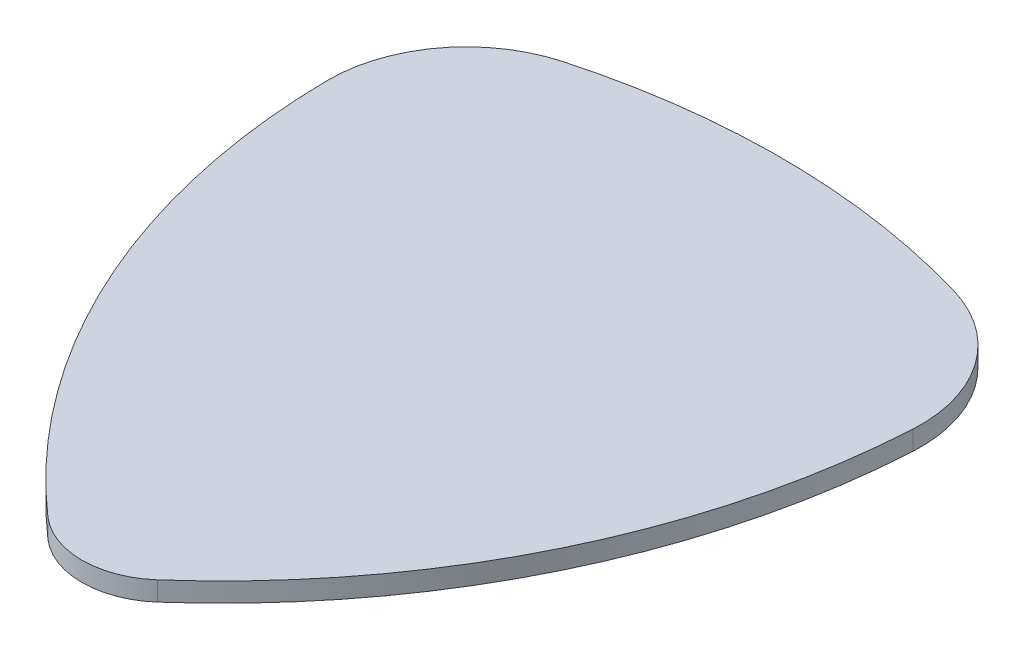
SolidWorks part; units mm, degrees
ref_plane "Front Plane" through (0, 0, 0) normal (0, 0, 1) x (1, 0, 0)
ref_plane "Top Plane" through (0, 0, 0) normal (0, 1, 0) x (1, 0, 0)
ref_plane "Right Plane" through (0, 0, 0) normal (1, 0, 0) x (0, 0, -1)
sketch "Sketch1" plane through (0, 0, 0) normal (0, 1, 0) x (1, 0, 0)
  arc A0 (0, 0) -> (21.3033, -0.2154) centre (10.4101, -24) cw
  arc A1 (0, 0) -> (10.4101, -24) centre (25.1455, -3.3508) ccw
  arc A2 (21.3033, -0.2154) -> (10.4101, -24) centre (-5.2207, -2.4543) cw
  dimension "D1" = 25.3678
  dimension "D2" = 24
extrude "Boss-Extrude1" add sketch "Sketch1" along normal blind 0.7
fillet "Fillet1" radius 5 1 edges at (21.3033, 0.35, 0.2154)
fillet "Fillet2" radius 5 1 edges at (0, 0.35, 0)
fillet "Fillet3" radius 3 1 edges at (10.4101, 0.35, 24)
scale "Scale1" scale about centroid uniform scaling yes scale factor 1.2
